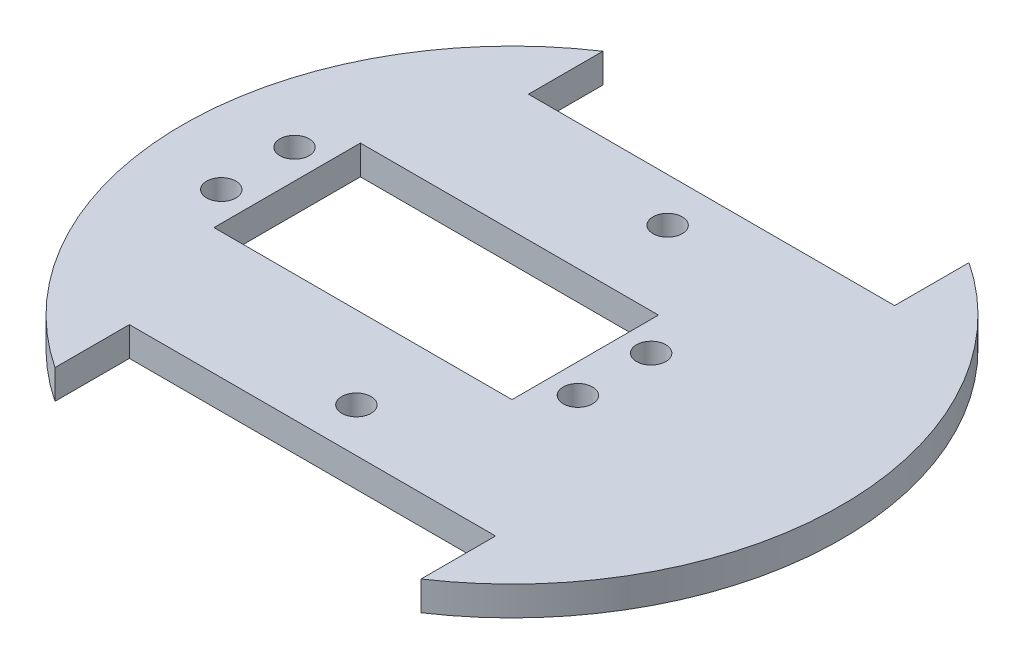
SolidWorks part; units mm, degrees
material "Acrílico (Impacto medio-alto)"
ref_plane "Piano frontale" through (0, 0, 0) normal (0, 0, 1) x (1, 0, 0)
ref_plane "Piano superiore" through (0, 0, 0) normal (0, 1, 0) x (1, 0, 0)
ref_plane "Piano destro" through (0, 0, 0) normal (1, 0, 0) x (0, 0, -1)
sketch "Schizzo1" plane through (0, 0, 0) normal (0, 1, 0) x (1, 0, 0)
  line L0 (-42.1632, 0) -> (43.9871, 0) construction
  line L1 (0, 27.25) -> (0, 0) construction
  line L2 (-25, 37.4166) -> (-25, 27.25)
  line L3 (-25, 27.25) -> (25, 27.25)
  line L4 (25, 37.4166) -> (25, 27.25)
  line L5 (0, 0) -> (0, -27.25) construction
  line L8 (-25, -37.4166) -> (-25, -27.25)
  line L9 (-25, -27.25) -> (25, -27.25)
  line L10 (25, -37.4166) -> (25, -27.25)
  arc A0 (-25, 37.4166) -> (-25, -37.4166) centre (0, 0) ccw
  arc A1 (25, -37.4166) -> (25, 37.4166) centre (0, 0) ccw
  point P3 (0, 45)
  point P8 (0, -45)
  dimension "D1" = 90
  dimension "D2" = 54.5
  dimension "D3" = 25
  dimension "D4" = 25
extrude "Estrusione-Estrusione1" add sketch "Schizzo1" along normal mid plane 4
sketch "Croquis1" plane through (0, -2, 0) normal (0, -1, 0) x (1, 0, 0)
  line L0 (-25, 27.25) -> (25, 27.25) construction
  line L1 (-11.5, 27.25) -> (-8.5, 27.25)
  line L2 (-11.5, 27.25) -> (-11.5, 19.25)
  line L3 (-11.5, 19.25) -> (-8.5, 19.25)
  line L4 (-8.5, 27.25) -> (-8.5, 19.25)
  line L5 (8.5, 27.25) -> (11.5, 27.25)
  line L6 (8.5, 27.25) -> (8.5, 19.25)
  line L7 (8.5, 19.25) -> (11.5, 19.25)
  line L8 (11.5, 27.25) -> (11.5, 19.25)
  line L9 (8.5, 31.25) -> (8.5, 27.25) construction
  line L10 (-11.5, 31.25) -> (-11.5, 27.25) construction
  line L11 (11.5, 27.25) -> (11.5, 31.25) construction
  line L12 (-12.75, 16.25) -> (-12.75, 19.25)
  line L13 (-12.75, 16.25) -> (-7.25, 16.25)
  line L14 (-12.75, 19.25) -> (-7.25, 19.25)
  line L15 (-7.25, 16.25) -> (-7.25, 19.25)
  line L16 (-12.75, 16.25) -> (-7.25, 19.25) construction
  line L17 (-12.75, 19.25) -> (-7.25, 16.25) construction
  line L18 (8.6009, 19.25) -> (11.3991, 19.25)
  line L19 (7.25, 16.25) -> (7.25, 19.25)
  line L20 (7.25, 16.25) -> (12.75, 16.25)
  line L21 (7.25, 19.25) -> (12.75, 19.25)
  line L22 (12.75, 16.25) -> (12.75, 19.25)
  line L23 (7.25, 16.25) -> (12.75, 19.25) construction
  line L24 (7.25, 19.25) -> (12.75, 16.25) construction
  line L25 (-45, 0) -> (45, 0) construction
  line L26 (-11.5, 16.25) -> (-8.5, 16.25)
  line L27 (-11.5, 16.25) -> (-11.5, 13.25)
  line L28 (-11.5, 13.25) -> (-8.5, 13.25)
  line L29 (-8.5, 16.25) -> (-8.5, 13.25)
  line L30 (8.5, 16.25) -> (11.5, 16.25)
  line L31 (8.5, 16.25) -> (8.5, 13.25)
  line L32 (8.5, 13.25) -> (11.5, 13.25)
  line L33 (11.5, 16.25) -> (11.5, 13.25)
  line L34 (7.25, -19.25) -> (12.75, -16.25) construction
  line L35 (7.25, -16.25) -> (12.75, -19.25) construction
  line L36 (-12.75, -19.25) -> (-7.25, -16.25) construction
  line L37 (-12.75, -16.25) -> (-7.25, -19.25) construction
  line L38 (11.5, -16.25) -> (11.5, -13.25)
  line L39 (8.5, -13.25) -> (11.5, -13.25)
  line L40 (8.5, -16.25) -> (8.5, -13.25)
  line L41 (8.5, -16.25) -> (11.5, -16.25)
  line L42 (-8.5, -16.25) -> (-8.5, -13.25)
  line L43 (-11.5, -13.25) -> (-8.5, -13.25)
  line L44 (-11.5, -16.25) -> (-11.5, -13.25)
  line L45 (-11.5, -16.25) -> (-8.5, -16.25)
  line L46 (12.75, -16.25) -> (12.75, -19.25)
  line L47 (7.25, -19.25) -> (12.75, -19.25)
  line L48 (7.25, -16.25) -> (12.75, -16.25)
  line L49 (7.25, -16.25) -> (7.25, -19.25)
  line L50 (8.6009, -19.25) -> (11.3991, -19.25)
  line L51 (-7.25, -16.25) -> (-7.25, -19.25)
  line L52 (-12.75, -19.25) -> (-7.25, -19.25)
  line L53 (-12.75, -16.25) -> (-7.25, -16.25)
  line L54 (-12.75, -16.25) -> (-12.75, -19.25)
  line L55 (11.5, -27.25) -> (11.5, -19.25)
  line L56 (8.5, -19.25) -> (11.5, -19.25)
  line L57 (8.5, -27.25) -> (8.5, -19.25)
  line L58 (8.5, -27.25) -> (11.5, -27.25)
  line L59 (-8.5, -27.25) -> (-8.5, -19.25)
  line L60 (-11.5, -19.25) -> (-8.5, -19.25)
  line L61 (-11.5, -27.25) -> (-11.5, -19.25)
  line L62 (-11.5, -27.25) -> (-8.5, -27.25)
  arc A0 (-25, 37.4166) -> (-25, -37.4166) centre (0, 0) ccw construction
  arc A1 (25, -37.4166) -> (25, 37.4166) centre (0, 0) ccw construction
  point P17 (-10, 17.75)
  point P18 (-10, 19.25)
  point P26 (10, 17.75)
  point P27 (10, 19.25)
  point P32 (10, 19.25)
  point P75 (10, -17.75)
  point P76 (-10, -17.75)
  dimension "D1" = 17
  dimension "D2" = 8
  dimension "D3" = 5.5
  dimension "D4" = 3
  dimension "D5" = 5.5
  dimension "D6" = 3
  dimension "D7" = 3
  dimension "D8" = 3
sketch "Croquis2" plane through (0, 2, 0) normal (0, 1, 0) x (1, 0, 0)
  line L7 (-30.7, 10) -> (10, 10)
  line L8 (-30.7, 10) -> (-30.7, -10)
  line L9 (-30.7, -10) -> (10, -10)
  line L11 (10, 10) -> (10, -10)
  circle A4 centre (-34.7, 5) radius 2 construction
  circle A5 centre (-34.7, -5) radius 2 construction
  circle A6 centre (14, 5) radius 2 construction
  circle A7 centre (14, -5) radius 2 construction
  circle A8 centre (-34.7, 5) radius 2
  circle A9 centre (-34.7, -5) radius 2
  circle A10 centre (14, 5) radius 2
  circle A11 centre (14, -5) radius 2
  circle A12 centre (0, 21.25) radius 2 construction
  circle A13 centre (0, -21.25) radius 2 construction
  circle A14 centre (0, 21.25) radius 2
  circle A15 centre (0, -21.25) radius 2
extrude "Cortar-Extruir1" cut sketch "Croquis2" against normal through all
